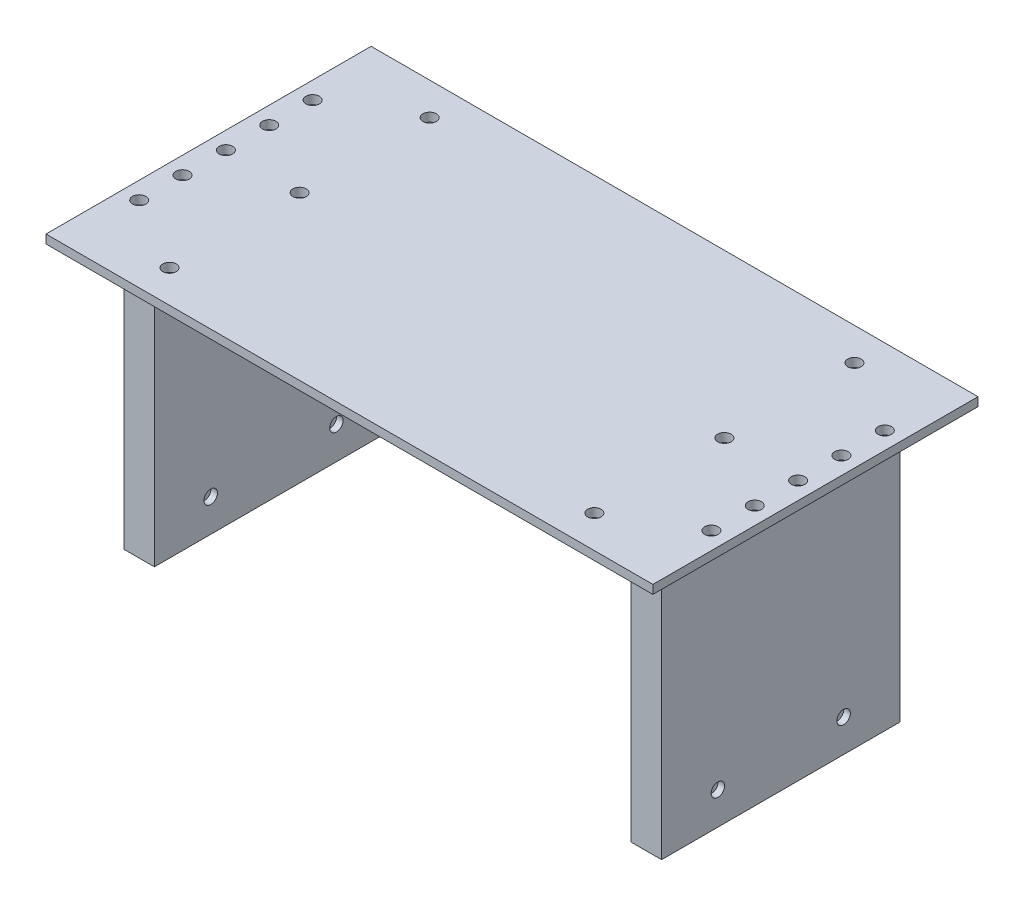
SolidWorks part; units mm, degrees
ref_plane "前视基准面" through (0, 0, 0) normal (0, 0, 1) x (1, 0, 0)
ref_plane "上视基准面" through (0, 0, 0) normal (0, 1, 0) x (1, 0, 0)
ref_plane "右视基准面" through (0, 0, 0) normal (1, 0, 0) x (0, 0, -1)
other "Configuration Table"
sketch "草图1" plane through (0, 0, 0) normal (0, 1, 0) x (1, 0, 0)
  line L0 (-70, 37.5) -> (70, 37.5)
  line L1 (70, 37.5) -> (70, -37.5)
  line L2 (70, -37.5) -> (-70, -37.5)
  line L3 (-70, -37.5) -> (-70, 37.5)
  line L4 (-70, 30) -> (-49, 30) construction
  line L5 (-70, 37.5) -> (70, -37.5) construction
  line L6 (-70, -37.5) -> (70, 37.5) construction
  line L7 (-49, 30) -> (-49, 37.5) construction
  line L8 (-49, 30) -> (-49, 0) construction
  line L9 (-49, 0) -> (-49, -30) construction
  line L10 (0, -55) -> (0, 55) construction
  line L11 (49, 30) -> (49, 0) construction
  line L12 (49, 0) -> (49, -30) construction
  point P2 (-55, 37.5)
  point P5 (-70, 30)
  point P6 (-49, 37.5)
  point P7 (0, 0)
  point P8 (-49, 30)
  point P10 (-49, 0)
  point P11 (-49, -30)
  dimension "D1" = 140
  dimension "D2" = 75
  dimension "D3" = 7.5
  dimension "D4" = 15
  dimension "D5" = 6
  dimension "D6" = 30
  dimension "D7" = 30
extrude "凸台-拉伸1" add sketch "草图1" along normal blind 2 contours L3 L0 L1 L2
sketch "草图2" plane through (0, 0, 0) normal (0, -1, 0) x (1, 0, 0)
  line L0 (-49, -30) -> (-49, 0) construction
  line L1 (-49, 0) -> (-49, 30) construction
  line L2 (49, -30) -> (49, 0) construction
  line L3 (49, 0) -> (49, 30) construction
  line L4 (-49, -30) -> (-49, 0) construction
  line L5 (-49, 0) -> (-49, 30) construction
  line L6 (49, -30) -> (49, 0) construction
  line L7 (49, 0) -> (49, 30) construction
  circle A0 centre (-49, 0) radius 1.55
  circle A1 centre (-49, -30) radius 1.55
  circle A2 centre (-49, 30) radius 1.55
  circle A3 centre (49, 30) radius 1.55
  circle A4 centre (49, 0) radius 1.55
  circle A5 centre (49, -30) radius 1.55
extrude "切除-拉伸1" cut sketch "草图2" against normal blind 3
sketch "草图3" plane through (0, 0, 0) normal (0, -1, 0) x (1, 0, 0)
  line L0 (-70, 37.5) -> (-70, -37.5) construction
  line L1 (70, 37.5) -> (-70, 37.5) construction
  line L2 (-70, -37.5) -> (70, -37.5) construction
  line L3 (0, -1.1) -> (0, 1.1) construction
  line L12 (-62, 27.5) -> (-62, -27.5)
  line L13 (-62, -27.5) -> (-55, -27.5)
  line L14 (-55, -27.5) -> (-55, 27.5)
  line L15 (-55, 27.5) -> (-62, 27.5)
  line L16 (55, -27.5) -> (55, 27.5)
  line L17 (62, -27.5) -> (55, -27.5)
  line L18 (62, 27.5) -> (62, -27.5)
  line L19 (55, 27.5) -> (62, 27.5)
  point P0 (-70, 27.5)
  point P5 (-70, -27.5)
  point P8 (-62, 27.5)
  point P11 (70, -27.5)
  point P12 (70, 27.5)
  point P15 (-62, -27.5)
  dimension "D1" = 10
  dimension "D2" = 10
  dimension "D3" = 8
  dimension "D4" = 8
  dimension "D5" = 10
  dimension "D6" = 55
  dimension "D7" = 7
extrude "凸台-拉伸2" add sketch "草图3" along normal blind 62
sketch "草图5" plane through (0, 0, 0) normal (0, -1, 0) x (1, 0, 0)
  line L0 (-62, 27.5) -> (-62, 37.5) construction
  line L1 (70, 37.5) -> (-70, 37.5) construction
  line L2 (-70, 37.5) -> (-70, -37.5) construction
  line L3 (-70, 27.5) -> (-62, 27.5) construction
  line L4 (1.1, 0) -> (-1.1, 0) construction
  line L5 (-70, -27.5) -> (-62, -27.5) construction
  line L6 (-66, 20) -> (-66, 0) construction
  line L7 (-66, 0) -> (-66, -20) construction
  line L8 (0, -1.1) -> (0, 1.1) construction
  line L9 (66, 0) -> (66, -20) construction
  line L10 (66, 20) -> (66, 0) construction
  circle A0 centre (-66, 20) radius 1.55
  circle A1 centre (-66, 10) radius 1.55
  circle A2 centre (-66, 0) radius 1.55
  circle A3 centre (-66, -10) radius 1.55
  circle A4 centre (-66, -20) radius 1.55
  circle A5 centre (66, -20) radius 1.55
  circle A6 centre (66, -10) radius 1.55
  circle A7 centre (66, 0) radius 1.55
  circle A8 centre (66, 10) radius 1.55
  circle A9 centre (66, 20) radius 1.55
  point P5 (-70, 27.5)
  point P13 (-66, 27.5)
  point P14 (-66, 20)
  point P15 (-66, 0)
  point P16 (-66, -20)
  point P17 (-66, 10)
  point P20 (-66, -10)
  point P41 (66, -10)
  point P42 (66, 10)
  point P43 (66, -20)
  point P44 (66, 0)
  point P45 (66, 20)
  dimension "D1" = 55
  dimension "D2" = 20
extrude "切除-拉伸2" cut sketch "草图5" against normal blind 15
sketch "草图6" plane through (-62, 0, 0) normal (-1, 0, 0) x (0, 0, 1)
  line L0 (-27.5, -62) -> (-27.5, 0) construction
  line L1 (-27.5, -31) -> (-27.5, -62) construction
  line L2 (0, -1.1) -> (0, 1.1) construction
  line L3 (27.5, -62) -> (27.5, 0) construction
  line L4 (-27.5, -46.5) -> (27.5, -46.5) construction
  line L5 (-27.5, -62) -> (0, -62) construction
  line L6 (27.5, -62) -> (-27.5, -62) construction
  line L7 (0, -62) -> (27.5, -62) construction
  line L8 (-18.9754, -46.5) -> (-18.9754, -62) construction
  line L9 (-27.5, -62) -> (-27.5, -22.7806) construction
  line L10 (-27.5, -22.7806) -> (-13.75, -22.7806) construction
  line L11 (-13.75, -22.7806) -> (-13.75, -62) construction
  line L12 (-20.625, -22.7806) -> (-20.625, -62) construction
  line L13 (-13.75, -22.7806) -> (0, -22.7806) construction
  line L14 (0, -22.7806) -> (0, -62) construction
  line L15 (-20.625, -59.5) -> (-20.625, -62) construction
  circle A1 centre (-14.5, -54.5) radius 1.55
  circle A4 centre (14.5, -54.5) radius 1.55
  point P0 (-27.5, -31)
  point P1 (-27.5, -62)
  point P7 (-27.5, -46.5)
  point P8 (0, -46.5)
  point P9 (27.5, -46.5)
  point P16 (0, -46.5)
  point P17 (-13.75, -62)
  point P18 (-27.5, -46.5)
  point P23 (13.75, -62)
  point P26 (-18.9754, -54.25)
  point P27 (-20.625, -22.7806)
  point P33 (-6.875, -62)
  point P34 (-20.625, -59.5)
  point P36 (-6.875, -22.7806)
  point P37 (-13.75, -59.5)
  point P38 (-6.875, -59.5)
  point P39 (0, -13.125)
  point P41 (6.875, -59.5)
  point P42 (13.75, -59.5)
  point P43 (20.625, -59.5)
  point P46 (-20.625, -62)
  point P47 (-20.625, -59.5)
  point P48 (17.0784, 0)
  dimension "D1" = 2.5
  dimension "D3" = 13
  dimension "D2" = 13
  dimension "D4" = 14.5
  dimension "D5" = 7.5
  dimension "D6" = 7.5
extrude "切除-拉伸3" cut sketch "草图6" against normal blind 15
mirror "镜向1" about plane through (0, 0, 0) normal (1, 0, 0) of "切除-拉伸3"
sketch "草图7" plane through (0, -62, 0) normal (0, -1, 0) x (1, 0, 0)
  line L0 (62, 27.5) -> (55, 27.5) construction
  line L1 (55, 27.5) -> (55, -27.5) construction
  line L2 (62, -27.5) -> (62, 27.5) construction
  line L3 (62, 27.5) -> (55, 27.5) construction
  line L4 (56.5, 26) -> (60.5, 26)
  line L5 (58.5, 27.5) -> (58.5, -26.3056) construction
  line L6 (1.1, 0) -> (-1.1, 0) construction
  line L7 (56.5, -26) -> (60.5, -26)
  line L8 (56.5, 26) -> (56.5, -26)
  line L9 (60.5, 26) -> (60.5, -26)
  line L10 (0, -1.1) -> (0, 1.1) construction
  line L11 (-56.5, 26) -> (-60.5, 26)
  line L12 (-56.5, 26) -> (-56.5, -26)
  line L13 (-56.5, -26) -> (-60.5, -26)
  line L14 (-60.5, 26) -> (-60.5, -26)
  point P0 (56.5, 26)
  point P5 (60.5, 25.5)
  dimension "D1" = 1.5
  dimension "D2" = 1.5
  dimension "D3" = 1.5
  dimension "D4" = 2
  dimension "D5" = 113
  dimension "D6" = 121
extrude "切除-拉伸4" cut sketch "草图7" against normal blind 20
